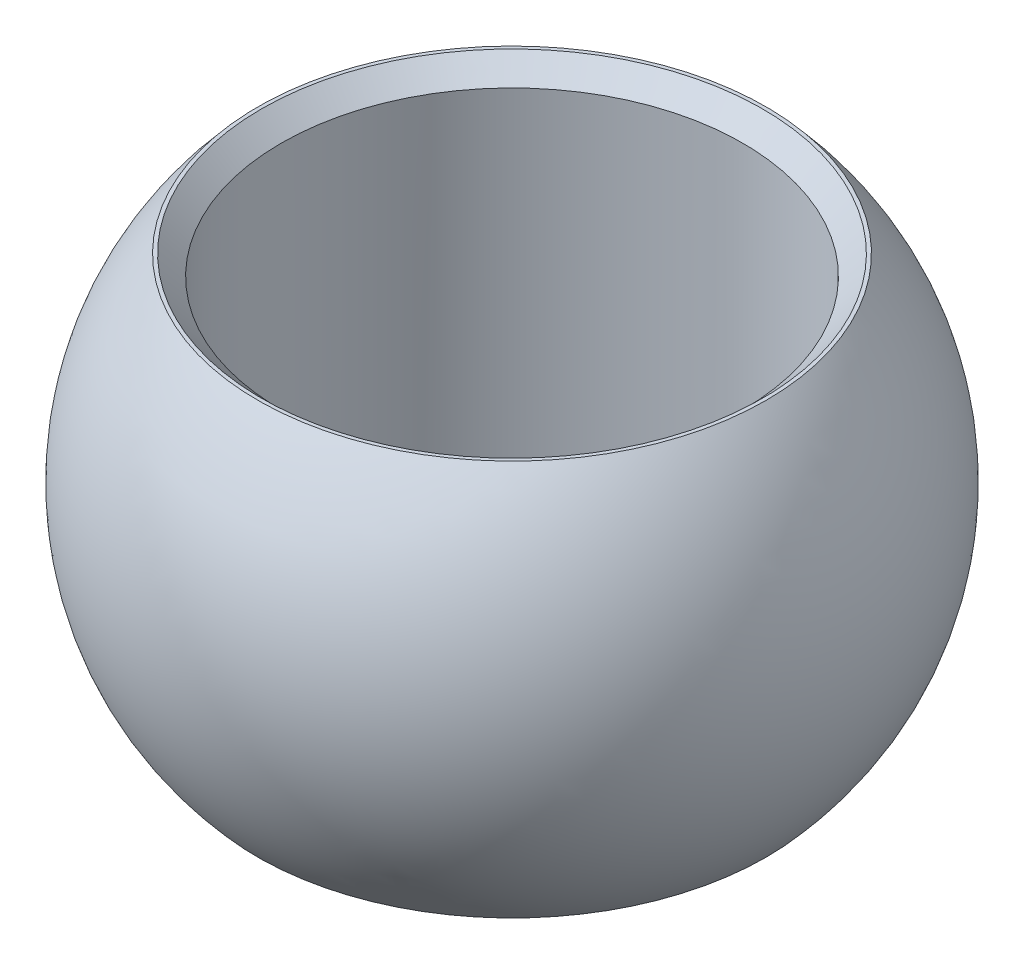
SolidWorks part; units mm, degrees
material "Custom Plastic"
ref_plane "Front Plane" through (0, 0, 0) normal (0, 0, 1) x (1, 0, 0)
ref_plane "Top Plane" through (0, 0, 0) normal (0, 1, 0) x (1, 0, 0)
ref_plane "Right Plane" through (0, 0, 0) normal (1, 0, 0) x (0, 0, -1)
sketch "Sketch1" plane through (0, 0, 0) normal (0, 0, 1) x (1, 0, 0)
  line L0 (0, -493.111) -> (0, 24162.4406) construction
  line L1 (17.5, 15) -> (17.5, -15)
  line L2 (17.5, -15) -> (19.2705, -15)
  line L3 (17.5, 15) -> (19.2705, 15)
  arc A0 (19.2705, 15) -> (19.2705, -15) centre (2.5, 0) cw
  point P9 (25, 0)
  point P10 (17.5, 0)
  dimension "D1" = 30
  dimension "D3" = 22.5
  dimension "D2" = 17.5
  dimension "D4" = 50
revolve "Revolve1" add sketch "Sketch1" angle 360 about L0
chamfer "Chamfer1" distance 1.5 angle 45 2 edges at (17.5, 15, 0) (17.5, -15, 0)
